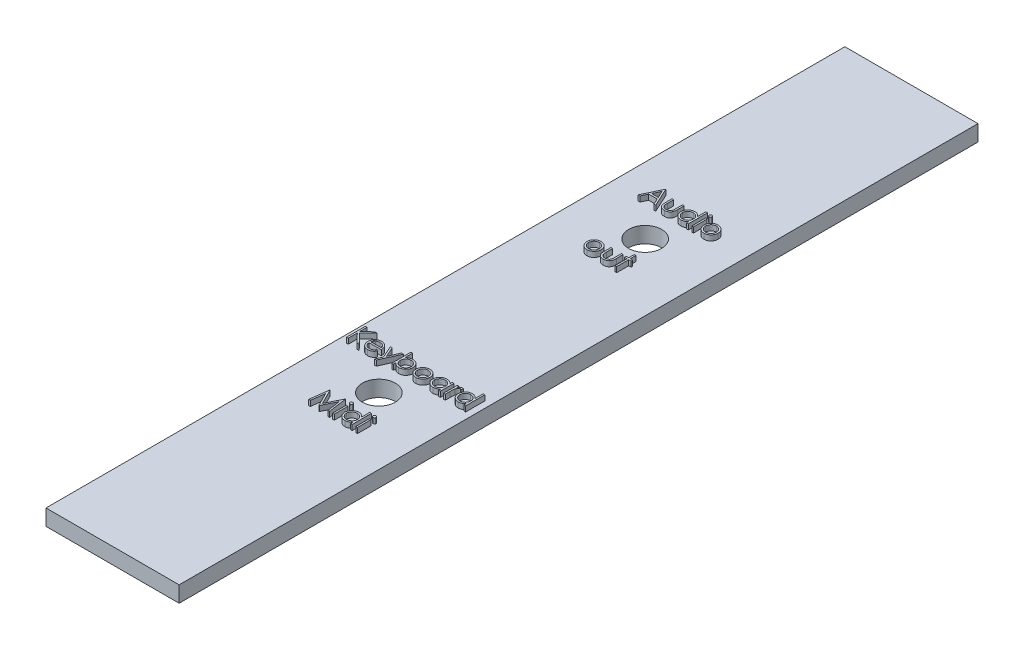
SolidWorks part; units mm, degrees
ref_plane "Front Plane" through (0, 0, 0) normal (0, 0, 1) x (1, 0, 0)
ref_plane "Top Plane" through (0, 0, 0) normal (0, 1, 0) x (1, 0, 0)
ref_plane "Right Plane" through (0, 0, 0) normal (1, 0, 0) x (0, 0, -1)
sketch "Sketch1" plane through (0, 0, 0) normal (0, 1, 0) x (1, 0, 0)
  line L0 (12.5, 0) -> (12.5, -50000) construction
  line L1 (0, 0) -> (25, 0)
  line L2 (0, 0) -> (0, -150)
  line L3 (0, -150) -> (25, -150)
  line L4 (25, 0) -> (25, -150)
  circle A0 centre (12.5, -50) radius 3.1
  circle A1 centre (12.5, -100) radius 3.1
  point P7 (12.5, 0)
  dimension "D3" = 6.2
  dimension "D4" = 6.2
  dimension "D1" = 25
  dimension "D2" = 150
  dimension "D5" = 50
  dimension "D6" = 50
extrude "Boss-Extrude1" add sketch "Sketch1" along normal blind 3
sketch "Sketch2" plane through (0, 3, 0) normal (0, 1, 0) x (1, 0, 0)
  line L0 (0, 0) -> (0, -150) construction
  line L1 (25, 0) -> (0, 0) construction
  line L2 (0, -150) -> (25, -150) construction
  text T0 "Audio\r\n\r\n  out"
  text T1 "Keyboard\r\n\r\n     Midi"
  dimension "D1" = 5.5
  dimension "D2" = 44.5
  dimension "D3" = 1
  dimension "D4" = 55
extrude "Boss-Extrude2" add sketch "Sketch2" along normal blind 1
